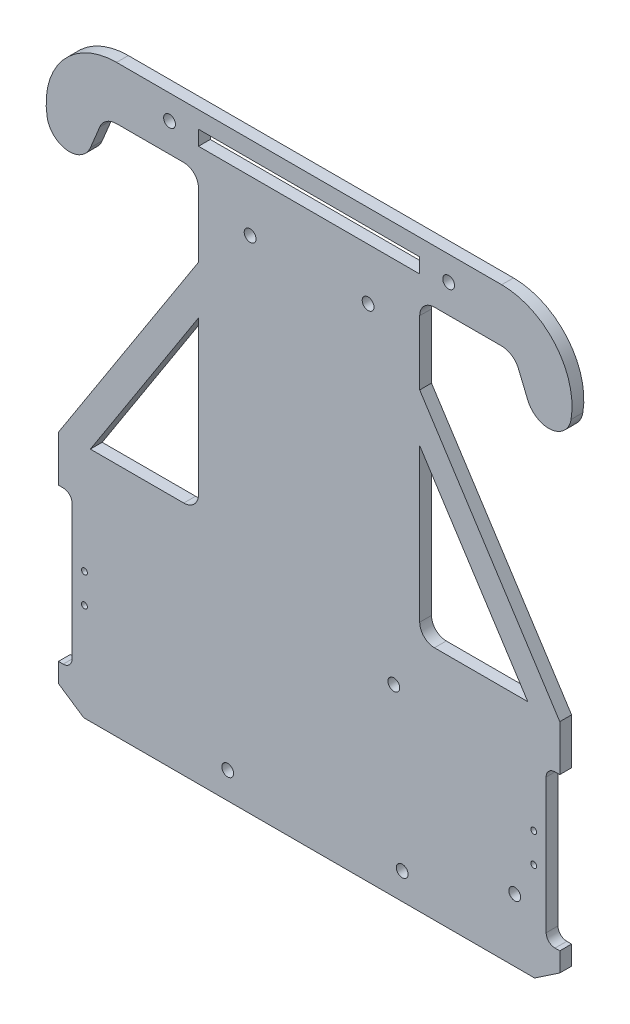
SolidWorks part; units mm, degrees
ref_plane "Front Plane" through (0, 0, 0) normal (0, 0, 1) x (1, 0, 0)
ref_plane "Top Plane" through (0, 0, 0) normal (0, 1, 0) x (1, 0, 0)
ref_plane "Right Plane" through (0, 0, 0) normal (1, 0, 0) x (0, 0, -1)
sketch "Sketch1" plane through (0, 0, 0) normal (0, 0, 1) x (1, 0, 0)
  line L0 (0, 200.9143) -> (0, -140.7937) construction
  line L1 (-210.6349, 0) -> (217.619, 0) construction
  line L2 (50, 140.7946) -> (-50, 140.7946)
  line L4 (-50.7073, 122.7946) -> (-42.5, 122.7946)
  line L5 (-37.5, 117.7946) -> (-37.5, 95.9981)
  line L6 (-42.5, 22.7946) -> (-74.161, 22.7946)
  line L7 (-85, 22.3446) -> (-85, -51.4566)
  line L8 (-76.4382, -57.2054) -> (76.4382, -57.2054)
  line L9 (0, -57.2054) -> (0, 140.7946)
  line L10 (85, 22.3446) -> (85, -51.4566)
  line L12 (37.5, 117.7946) -> (37.5, 95.9981)
  line L13 (50.7073, 122.7946) -> (42.5, 122.7946)
  line L15 (-50, 140.7946) -> (-65.2939, 140.7946)
  line L16 (-74.161, 111.3055) -> (-70.9654, 118.9965)
  line L17 (-65.2744, 122.7946) -> (-50.7073, 122.7946)
  line L18 (65.2744, 122.7946) -> (50.7073, 122.7946)
  line L19 (74.161, 111.3055) -> (70.9654, 118.9965)
  line L20 (50, 140.7946) -> (65.2939, 140.7946)
  line L21 (-85, 22.3446) -> (-37.5, 95.9981)
  line L22 (-74.161, 22.7946) -> (-37.5, 79.6411)
  line L23 (74.161, 22.7946) -> (37.5, 79.6411)
  line L24 (85, 22.3446) -> (37.5, 95.9981)
  line L25 (-37.5, 79.6411) -> (-37.5, 27.7946)
  line L26 (37.5, 79.6411) -> (37.5, 27.7946)
  line L27 (74.161, 22.7946) -> (42.5, 22.7946)
  line L28 (-85, -51.4566) -> (-76.4382, -57.2054)
  line L29 (85, -51.4566) -> (76.4382, -57.2054)
  arc A0 (-65.2939, 140.7946) -> (-88.823, 112.9782) centre (-65.2939, 116.9351) ccw
  arc A1 (-88.823, 112.9782) -> (-74.161, 111.3055) centre (-81.2513, 114.2515) ccw
  arc A2 (-70.9654, 118.9965) -> (-65.2744, 122.7946) centre (-65.2744, 116.6319) cw
  arc A3 (70.9654, 118.9965) -> (65.2744, 122.7946) centre (65.2744, 116.6319) ccw
  arc A4 (88.823, 112.9782) -> (74.161, 111.3055) centre (81.2513, 114.2515) cw
  arc A5 (65.2939, 140.7946) -> (88.823, 112.9782) centre (65.2939, 116.9351) cw
  arc A6 (-42.5, 122.7946) -> (-37.5, 117.7946) centre (-42.5, 117.7946) cw
  arc A7 (37.5, 117.7946) -> (42.5, 122.7946) centre (42.5, 117.7946) cw
  arc A8 (-37.5, 27.7946) -> (-42.5, 22.7946) centre (-42.5, 27.7946) cw
  arc A9 (37.5, 27.7946) -> (42.5, 22.7946) centre (42.5, 27.7946) ccw
  point P43 (-37.5, 122.7946)
  point P46 (37.5, 122.7946)
  point P49 (-37.5, 22.7946)
  point P52 (37.5, 22.7946)
  dimension "D8" = 5
  dimension "D9" = 5
  dimension "D10" = 5
  dimension "D11" = 5
  dimension "D1" = 118
  dimension "D2" = 37.5
  dimension "D3" = 85
  dimension "D4" = 50
  dimension "D5" = 18
  dimension "D7" = 36.661
extrude "Boss-Extrude1" add sketch "Sketch1" along normal blind 4
sketch "Sketch3" plane through (0, 0, 4) normal (0, 0, 1) x (1, 0, 0)
  line L0 (0, -68.1919) -> (0, 197.0744) construction
  line L3 (0, 137.2085) -> (0, 125.2085)
  circle A0 centre (-47.3247, 132.5348) radius 2
  circle A1 centre (47.3247, 132.5348) radius 2
extrude "Cut-Extrude1" cut sketch "Sketch3" against normal blind 10 contours A0 | A1
sketch "Sketch4" plane through (0, 0, 4) normal (0, 0, 1) x (1, 0, 0)
  line L0 (0, -44.9495) -> (0, 125.7716) construction
  line L1 (-99.472, 6.7926) -> (-83.38, 6.7926)
  line L2 (-99.472, 6.7926) -> (-99.472, -44.9495)
  line L3 (-99.472, -44.9495) -> (-83.38, -44.9495)
  line L4 (-80.38, 3.7926) -> (-80.38, -41.9495)
  line L5 (99.472, -44.9495) -> (83.38, -44.9495)
  line L6 (99.472, 6.7926) -> (99.472, -44.9495)
  line L7 (99.472, 6.7926) -> (83.38, 6.7926)
  line L8 (80.38, 3.7926) -> (80.38, -41.9495)
  arc A0 (83.38, -44.9495) -> (80.38, -41.9495) centre (83.38, -41.9495) cw
  arc A1 (83.38, 6.7926) -> (80.38, 3.7926) centre (83.38, 3.7926) ccw
  arc A2 (-83.38, -44.9495) -> (-80.38, -41.9495) centre (-83.38, -41.9495) ccw
  arc A3 (-80.38, 3.7926) -> (-83.38, 6.7926) centre (-83.38, 3.7926) ccw
  point P13 (80.38, -44.9495)
  point P16 (80.38, 6.7926)
  point P19 (-80.38, -44.9495)
  point P22 (-80.38, 6.7926)
  dimension "D1" = 3
extrude "Cut-Extrude2" cut sketch "Sketch4" against normal blind 10
sketch "Sketch5" plane through (0, 0, 4) normal (0, 0, 1) x (1, 0, 0)
  line L0 (0, 179.5319) -> (0, -136.1608) construction
  line L1 (-37.5, 112.5677) -> (33.2423, 112.5677) construction
  line L2 (37.5, 135.0519) -> (-37.5, 135.0519)
  line L3 (0, 135.0519) -> (0, 130.0519)
  line L4 (37.5, 130.0519) -> (-37.5, 130.0519)
  line L5 (-37.5, 135.0519) -> (-37.5, 130.0519)
  line L6 (-37.5, 117.7946) -> (-37.5, 95.9981) construction
  line L7 (37.5, 135.0519) -> (37.5, 130.0519)
  circle A0 centre (-20, 112.5677) radius 2
  circle A1 centre (20, 112.5677) radius 2
  dimension "D3" = 20
  dimension "D1" = 5
  dimension "D2" = 37.5
extrude "Cut-Extrude3" cut sketch "Sketch5" against normal blind 10 contours L2 L5 L4 L3 | L7 L2 L3 L4 | A1 | A0
sketch "Sketch6" plane through (0, 0, 4) normal (0, 0, 1) x (1, 0, 0)
  line L0 (28.7288, 10.6018) -> (28.7288, -3.2776) construction
  line L5 (20.9528, 5.097) -> (39.1108, 5.097) construction
  line L6 (74.6963, -35.903) -> (60.1908, -35.903) construction
  line L7 (69.7288, -29.0536) -> (69.7288, -40.4285) construction
  circle A0 centre (28.7288, 5.097) radius 2
  circle A1 centre (69.7288, -35.903) radius 2
extrude "Cut-Extrude4" cut sketch "Sketch6" against normal blind 10
sketch "Sketch7" plane through (0, 0, 4) normal (0, 0, 1) x (1, 0, 0)
  line L0 (-112.4767, -19.1074) -> (-33.6185, -19.1074)
  line L1 (-83.38, 6.7926) -> (-85, 6.7926) construction
  line L3 (-76.1772, -10.7546) -> (-76.1772, -26.4709) construction
  line L4 (0, 89.7089) -> (0, -132.7121) construction
  circle A0 centre (-76.1772, -14.1074) radius 1
  circle A1 centre (-76.1772, -24.1074) radius 1
  circle A2 centre (76.1772, -24.1074) radius 1
  circle A3 centre (76.1772, -14.1074) radius 1
  dimension "D2" = 5
  dimension "D1" = 25.9
extrude "Cut-Extrude5" cut sketch "Sketch7" against normal blind 10 contours A0 | A1 | A2 | A3
sketch "Sketch8" plane through (0, 0, 4) normal (0, 0, 1) x (1, 0, 0)
  line L0 (-94.2148, -48.1995) -> (127.1416, -48.1995) construction
  line L1 (-85, -44.9495) -> (-85, -51.4566) construction
  line L2 (85, -44.9495) -> (85, -51.4566) construction
  circle A0 centre (-27.6, -48.1995) radius 2
  circle A1 centre (31.57, -48.1995) radius 2
  dimension "D2" = 57.4
  dimension "D1" = 3.25
  dimension "D3" = 53.43
extrude "Cut-Extrude6" cut sketch "Sketch8" against normal blind 10
